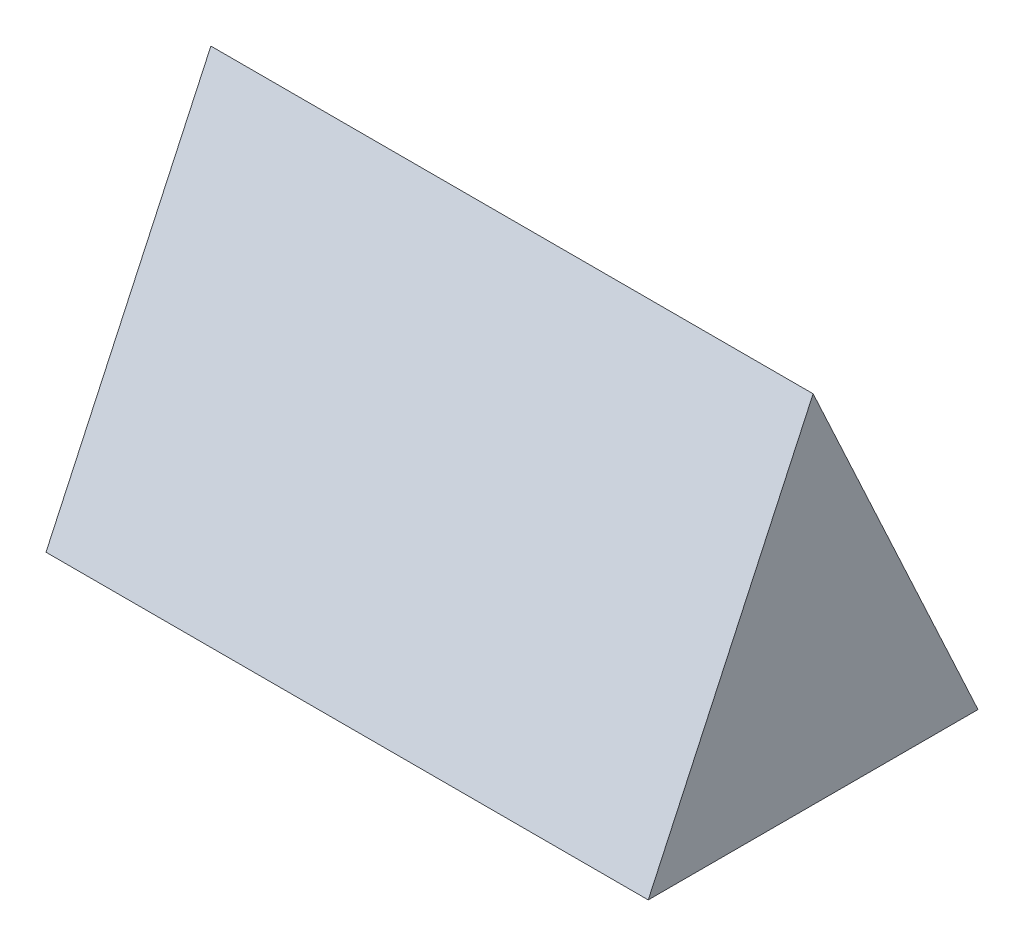
SolidWorks part; units mm, degrees
ref_plane "Front Plane" through (0, 0, 0) normal (0, 0, 1) x (1, 0, 0)
ref_plane "Top Plane" through (0, 0, 0) normal (0, 1, 0) x (1, 0, 0)
ref_plane "Right Plane" through (0, 0, 0) normal (1, 0, 0) x (0, 0, -1)
sketch "Sketch1" plane through (0, 0, 0) normal (0, 0, 1) x (1, 0, 0)
  line L0 (-185.3412, -69.1215) -> (164.6588, -69.1215)
  line L1 (-185.3412, -69.1215) -> (-185.3412, -31.0215)
  line L2 (164.6588, -69.1215) -> (164.6588, -31.0215)
  line L3 (-185.3412, -31.0215) -> (-147.2412, -31.0215)
  line L4 (164.6588, -31.0215) -> (81.5588, -31.0215)
  line L5 (-147.2412, -69.1215) -> (-147.2412, 130.8785)
  line L6 (119.6088, -31.0215) -> (164.6588, -31.0215) construction
  line L7 (144.6588, -31.0215) -> (144.6588, -13.3431) construction
  line L8 (74.0588, 24.9785) -> (89.0588, 24.9785)
  line L9 (74.0588, 24.9785) -> (74.0588, -38.5215)
  line L10 (74.0588, -38.5215) -> (89.0588, -38.5215)
  line L11 (89.0588, 24.9785) -> (89.0588, -38.5215)
  line L12 (144.6588, -31.0215) -> (89.0588, 24.9785)
  line L13 (-94.1412, -31.0215) -> (-94.1412, -28.5215)
  line L14 (-94.1412, -31.0215) -> (-94.1412, -28.5215)
  line L15 (-94.1412, -31.0215) -> (-109.1412, -31.0215) construction
  line L16 (23.5088, -33.5215) -> (33.5088, -33.5215)
  line L17 (33.5088, -31.0215) -> (43.5088, -31.0215) construction
  line L18 (-94.1412, -28.5215) -> (23.5088, -28.5215)
  line L19 (81.5588, -31.0215) -> (108.4642, -4.1161) construction
  line L20 (-94.1412, -31.0215) -> (-94.1412, -33.5215)
  line L22 (-94.1412, -33.5215) -> (23.5088, -33.5215)
  line L23 (74.0588, 24.9785) -> (74.0588, 14.9785) construction
  line L25 (33.5088, -33.5215) -> (33.5088, -28.5215)
  circle A0 centre (-147.2412, -31.0215) radius 38.1
  circle A2 centre (81.5588, -31.0215) radius 38.05
  arc A3 (74.0588, 24.9785) -> (23.5088, -28.5215) centre (75.5338, -27.0465) ccw
  arc A4 (74.0588, 14.9785) -> (33.5088, -28.5215) centre (75.5338, -27.0465) ccw
  dimension "D7" = 117.65
  dimension "D1" = 350
  dimension "D2" = 38.1
  dimension "D3" = 38.1
  dimension "D4" = 38.1
  dimension "D5" = 83.1
  dimension "D6" = 200
  dimension "D8" = 45.05
  dimension "D9" = 7.5
  dimension "D10" = 7.5
  dimension "D11" = 7.5
  dimension "D12" = 45.05
  dimension "D13" = 25.05
  dimension "D14" = 20
  dimension "D15" = 15
  dimension "D16" = 63.5
  dimension "D17" = 6.7283
  dimension "D18" = 10
  dimension "D20" = 10
sketch "Sketch2" plane through (0, 0, 0) normal (1, 0, 0) x (0, 0, -1)
  line L0 (0, -31.0215) -> (-75, -31.0215)
  line L1 (0, 7.0785) -> (0, -69.1215) construction
  line L2 (0, -31.0215) -> (75, -31.0215)
  line L3 (0, 130.8785) -> (-75, -31.0215)
  line L4 (0, -69.1215) -> (0, 130.8785) construction
  line L5 (0, 130.8785) -> (75, -31.0215)
  dimension "D1" = 75
  dimension "D2" = 75
extrude "Boss-Extrude2" add sketch "Sketch2" along normal blind 126.95 and the other way blind 147
